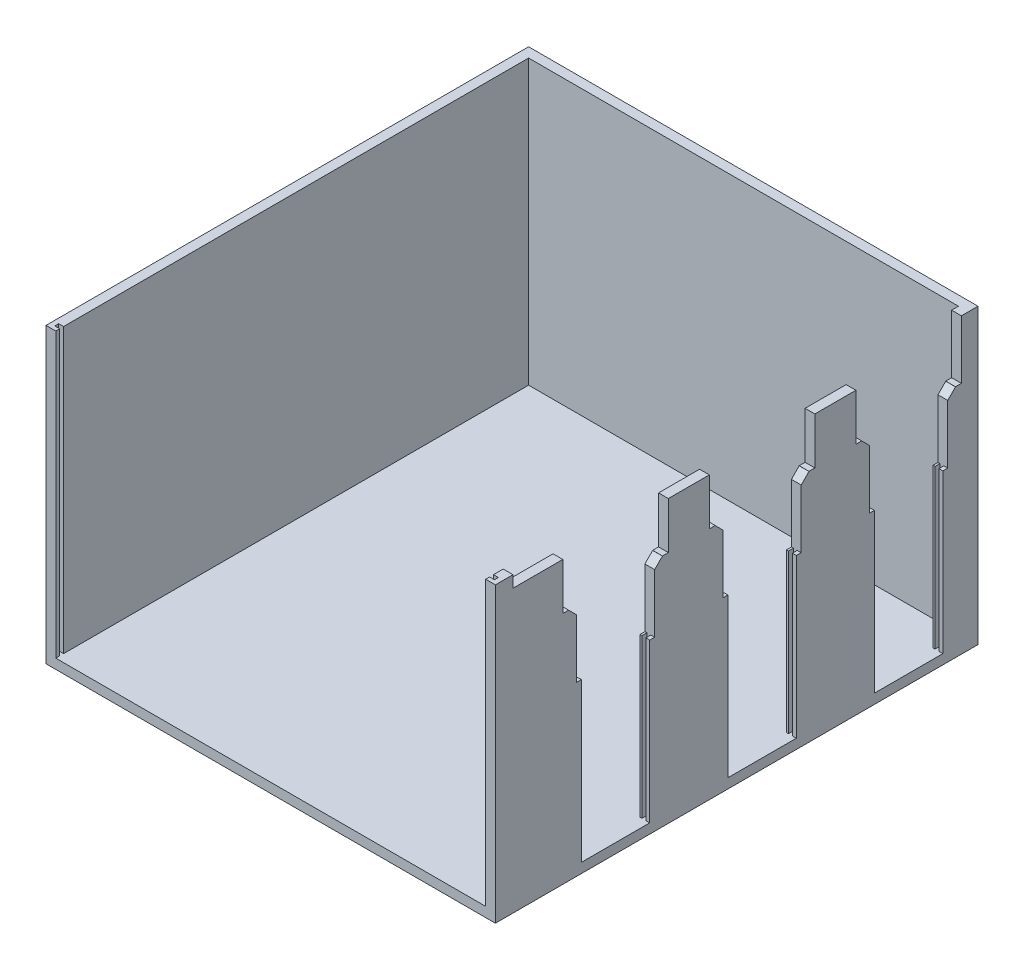
SolidWorks part; units mm, degrees
ref_plane "Płaszczyzna przednia" through (0, 0, 0) normal (0, 0, 1) x (1, 0, 0)
ref_plane "Płaszczyzna górna" through (0, 0, 0) normal (0, 1, 0) x (1, 0, 0)
ref_plane "Płaszczyzna prawa" through (0, 0, 0) normal (1, 0, 0) x (0, 0, -1)
sketch "Szkic1" plane through (0, 0, 0) normal (0, 0, 1) x (1, 0, 0)
  line L1 (-115, -75) -> (115, -75)
  line L2 (-115, -75) -> (-115, 75)
  line L3 (-115, 75) -> (115, 75)
  line L4 (115, -75) -> (115, 75)
  line L5 (0, 75) -> (0, -75) construction
  line L6 (-115, 0) -> (115, 0) construction
  point P0 (0, 0)
  dimension "D1" = 230
  dimension "D2" = 150
extrude "Dodanie-wyciągnięcie1" add sketch "Szkic1" along normal blind 5
sketch "Szkic3" plane through (0, 0, 5) normal (0, 0, 1) x (1, 0, 0)
  line L4 (115, -75) -> (115, 75)
  line L5 (115, 75) -> (-115, 75)
  line L6 (-115, 75) -> (-115, -75)
  line L7 (-115, -75) -> (115, -75)
  line L8 (115, -75) -> (115, 75)
  line L9 (115, 75) -> (110, 75)
  line L10 (-115, 75) -> (-115, -75)
  line L11 (-115, -75) -> (115, -75)
  line L12 (-110, 70) -> (-110, 75)
  line L13 (110, 70) -> (110, 75)
  line L14 (-110, 75) -> (-115, 75)
  line L16 (110, -70) -> (110, 70)
  line L17 (110, 70) -> (-110, 70)
  line L18 (-110, 70) -> (-110, -70)
  line L19 (-110, -70) -> (110, -70)
  line L20 (110, -70) -> (110, 70)
  line L22 (-110, 70) -> (-110, -70)
  line L23 (-110, -70) -> (110, -70)
  dimension "D1" = 0
  dimension "D2" = 5
extrude "Dodanie-wyciągnięcie2" add sketch "Szkic3" along normal blind 242
sketch "Szkic4" plane through (115, 0, 0) normal (1, 0, 0) x (0, 0, -1)
  line L0 (-247, 75) -> (0, 75) construction
  line L1 (-238, 75) -> (-208, 75)
  line L2 (-163, 75) -> (-133, 75)
  line L3 (-88, 75) -> (-58, 75)
  line L16 (-133, 69) -> (-163, 69)
  line L17 (-163, 69) -> (-163, 93)
  line L18 (-163, 93) -> (-208, 93)
  line L19 (-208, 93) -> (-208, 69)
  line L20 (-208, 69) -> (-238, 69)
  line L21 (-238, 69) -> (-238, 93)
  line L22 (-238, 93) -> (-242, 93)
  line L23 (-242, 93) -> (-242, 65)
  line L24 (-242, 65) -> (-5, 65)
  line L25 (-5, 65) -> (-5, 93)
  line L26 (-5, 93) -> (-58, 93)
  line L27 (-58, 93) -> (-58, 69)
  line L28 (-58, 69) -> (-88, 69)
  line L29 (-88, 69) -> (-88, 93)
  line L30 (-88, 93) -> (-133, 93)
  line L31 (-133, 93) -> (-133, 69)
  line L32 (-133, 69) -> (-163, 69)
  line L33 (-163, 69) -> (-163, 75)
  line L35 (-208, 75) -> (-208, 69)
  line L36 (-208, 69) -> (-238, 69)
  line L37 (-238, 69) -> (-238, 75)
  line L43 (-58, 75) -> (-58, 69)
  line L44 (-58, 69) -> (-88, 69)
  line L45 (-88, 69) -> (-88, 75)
  line L47 (-133, 75) -> (-133, 69)
  dimension "D1" = 0
extrude "Wytnij-wyciągnięcie1" cut sketch "Szkic4" against normal up to next
sketch "Szkic6" plane through (115, 0, 0) normal (1, 0, 0) x (0, 0, -1)
  line L0 (-62.5, 65) -> (-62.5, 69)
  line L1 (-59.5, 45.0546) -> (-59.5, 45)
  line L2 (-8.5, 65) -> (-8.5, 75)
  line L3 (-137.5, 65) -> (-137.5, 69)
  line L4 (-58.5, 44) -> (-55.5, 41)
  line L5 (-55.5, 41) -> (-54.5, 41)
  line L6 (-54.5, 41) -> (-54.5, 44)
  line L7 (-54.5, 44) -> (-58.5, 44)
  line L8 (-58.5, 44) -> (-55.5, 41)
  line L12 (-62.5, 65) -> (-62.5, 45.0546)
  line L13 (-62.5, 45.0546) -> (-55.7121, 45.0546)
  line L14 (-55.7121, 45.0546) -> (-55.7121, 45.7879)
  line L15 (-55.7121, 45.7879) -> (-59.8, 49.8757)
  line L16 (-59.8, 49.8757) -> (-59.8, 51)
  line L17 (-59.8, 51) -> (-11.2, 51)
  line L18 (-11.2, 51) -> (-11.2, 49.8757)
  line L19 (-11.2, 49.8757) -> (-15.2879, 45.7879)
  line L20 (-15.5, 41) -> (-16.5, 41)
  line L21 (-16.5, 41) -> (-16.5, 51)
  line L22 (-16.5, 51) -> (-20.5, 51)
  line L23 (-20.5, 51) -> (-20.5, 50.5)
  line L24 (-20.5, 50.5) -> (-18.2071, 48.2071)
  line L25 (-18.2071, 46.7929) -> (-20.5, 44.5)
  line L26 (-20.5, 44.5) -> (-39.5, 44.5)
  line L27 (-39.5, 44.5) -> (-39.5, 34.5)
  line L28 (-39.5, 34.5) -> (-43.5, 34.5)
  line L29 (-43.5, 34.5) -> (-43.5, 44.5)
  line L30 (-43.5, 44.5) -> (-50.5, 44.5)
  line L31 (-50.5, 44.5) -> (-52.7929, 46.7929)
  line L32 (-52.7929, 48.2071) -> (-50.5, 50.5)
  line L33 (-50.5, 50.5) -> (-50.5, 51)
  line L34 (-50.5, 51) -> (-54.5, 51)
  line L35 (-54.5, 51) -> (-54.5, 41)
  line L36 (-54.5, 41) -> (-55.5, 41)
  line L37 (-55.5, 41) -> (-55.5, 11)
  line L38 (-55.5, 11) -> (-15.5, 11)
  line L39 (-15.5, 11) -> (-15.5, 41)
  line L57 (-55.5, 41) -> (-55.5, 11)
  line L58 (-55.5, 11) -> (-15.5, 11)
  line L59 (-15.5, 11) -> (-15.5, 41)
  line L60 (-15.2879, 45.7879) -> (-15.2879, 45.0546)
  line L61 (-15.2879, 45.0546) -> (-8.5, 45.0546)
  line L62 (-8.5, 45.0546) -> (-8.5, 65)
  line L63 (-8.5, 65) -> (-62.5, 65)
  line L64 (-62.5, 65) -> (-62.5, 45.0546)
  line L65 (-62.5, 45.0546) -> (-59.5, 45.0546)
  line L73 (-11.5, 45.0546) -> (-8.5, 45.0546)
  line L74 (-8.5, 45.0546) -> (-8.5, 65)
  line L76 (-15.5, 41) -> (-12.5, 44)
  line L77 (-12.5, 44) -> (-16.5, 44)
  line L78 (-16.5, 44) -> (-16.5, 41)
  line L79 (-16.5, 41) -> (-15.5, 41)
  line L80 (-15.5, 41) -> (-12.5, 44)
  line L84 (-134.5, 45.0546) -> (-134.5, 45)
  line L85 (-59.5, 45) -> (-58.5, 44)
  line L86 (-58.5, 44) -> (-54.5, 44)
  line L87 (-54.5, 44) -> (-54.5, 51)
  line L88 (-54.5, 51) -> (-59.5, 51)
  line L89 (-59.5, 51) -> (-59.5, 45)
  line L90 (-59.5, 45) -> (-58.5, 44)
  line L95 (-16.5, 51) -> (-16.5, 44)
  line L96 (-16.5, 44) -> (-12.5, 44)
  line L97 (-12.5, 44) -> (-11.5, 45)
  line L98 (-11.5, 45) -> (-11.5, 51)
  line L99 (-11.5, 51) -> (-16.5, 51)
  line L102 (-12.5, 44) -> (-11.5, 45)
  line L103 (-11.5, 45) -> (-11.5, 45.0546)
  line L105 (-83.5, 65) -> (-83.5, 69)
  line L106 (-133.5, 44) -> (-130.5, 41)
  line L107 (-130.5, 41) -> (-130.5, 11)
  line L108 (-130.5, 11) -> (-90.5, 11)
  line L109 (-90.5, 11) -> (-90.5, 41)
  line L110 (-137.5, 65) -> (-137.5, 45.0546)
  line L111 (-137.5, 45.0546) -> (-134.5, 45.0546)
  line L112 (-86.5, 45.0546) -> (-83.5, 45.0546)
  line L113 (-83.5, 45.0546) -> (-83.5, 65)
  line L114 (-90.5, 41) -> (-87.5, 44)
  line L115 (-134.5, 45) -> (-133.5, 44)
  line L116 (-87.5, 44) -> (-86.5, 45)
  line L117 (-58, 69) -> (-88, 69)
  line L118 (-88, 69) -> (-88, 75)
  line L119 (-88, 75) -> (-133, 75)
  line L120 (-133, 75) -> (-133, 69)
  line L121 (-133, 69) -> (-163, 69)
  line L122 (-163, 69) -> (-163, 75)
  line L123 (-163, 75) -> (-208, 75)
  line L124 (-208, 75) -> (-208, 69)
  line L125 (-208, 69) -> (-238, 69)
  line L126 (-238, 69) -> (-238, 75)
  line L127 (-238, 75) -> (-247, 75)
  line L128 (-247, 75) -> (-247, -75)
  line L129 (-247, -75) -> (0, -75)
  line L130 (0, -75) -> (0, 75)
  line L131 (0, 75) -> (-58, 75)
  line L132 (-58, 75) -> (-58, 69)
  line L133 (-58, 69) -> (-62.5, 69)
  line L134 (-88, 69) -> (-88, 75)
  line L135 (-88, 75) -> (-133, 75)
  line L136 (-133, 75) -> (-133, 69)
  line L137 (-133, 69) -> (-137.5, 69)
  line L138 (-163, 69) -> (-163, 75)
  line L139 (-163, 75) -> (-208, 75)
  line L140 (-208, 75) -> (-208, 69)
  line L141 (-208, 69) -> (-212.5, 69)
  line L147 (-8.5, 75) -> (-58, 75)
  line L148 (-58, 75) -> (-58, 69)
  line L149 (-86.5, 45) -> (-86.5, 45.0546)
  line L150 (-133, 75) -> (-133, 69)
  line L151 (-212.5, 65) -> (-212.5, 69)
  line L152 (-209.5, 45.0546) -> (-209.5, 45)
  line L153 (-158.5, 65) -> (-158.5, 69)
  line L154 (-208.5, 44) -> (-205.5, 41)
  line L155 (-205.5, 41) -> (-205.5, 11)
  line L156 (-205.5, 11) -> (-165.5, 11)
  line L157 (-165.5, 11) -> (-165.5, 41)
  line L158 (-212.5, 65) -> (-212.5, 45.0546)
  line L159 (-212.5, 45.0546) -> (-209.5, 45.0546)
  line L160 (-161.5, 45.0546) -> (-158.5, 45.0546)
  line L161 (-158.5, 45.0546) -> (-158.5, 65)
  line L162 (-165.5, 41) -> (-162.5, 44)
  line L163 (-209.5, 45) -> (-208.5, 44)
  line L164 (-162.5, 44) -> (-161.5, 45)
  line L165 (-161.5, 45) -> (-161.5, 45.0546)
  line L166 (-208, 75) -> (-208, 69)
  line L167 (-83.5, 69) -> (-88, 69)
  line L168 (-158.5, 69) -> (-163, 69)
  arc A2 (-18.2071, 46.7929) -> (-18.2071, 48.2071) centre (-18.9142, 47.5) ccw
  arc A3 (-52.7929, 48.2071) -> (-52.7929, 46.7929) centre (-52.0858, 47.5) ccw
  dimension "D9" = 75
  dimension "D1" = 0
  dimension "D2" = 0
  dimension "D3" = 0
  dimension "D4" = 0
  dimension "D5" = 0
  dimension "D6" = 0
  dimension "D7" = 0
  dimension "D8" = 3
extrude "Wytnij-wyciągnięcie2" cut sketch "Szkic6" against normal up to surface (5 mm away)
sketch "Szkic7" plane through (0, 75, 0) normal (0, 1, 0) x (1, 0, 0)
  line L0 (-110, -245) -> (-112.5, -245)
  line L1 (-110, -247) -> (-110, -5) construction
  line L2 (-112.5, -245) -> (-112.5, -243)
  line L3 (-112.5, -243) -> (-110, -243)
  line L4 (-110, -247) -> (-110, -5) construction
  line L5 (-110, -247) -> (-115, -247) construction
  line L6 (-110, -243) -> (-110, -245)
  line L7 (0, -247) -> (0, -5) construction
  line L8 (110, -247) -> (-110, -247) construction
  line L9 (110, -5) -> (-110, -5) construction
  line L10 (110, -243) -> (110, -245)
  line L11 (112.5, -243) -> (110, -243)
  line L12 (112.5, -245) -> (112.5, -243)
  line L13 (110, -245) -> (112.5, -245)
  line L14 (111, -205.5) -> (111, -203)
  line L16 (113, -203) -> (113, -205.5)
  line L17 (110, -185.5) -> (115, -185.5) construction
  line L18 (110, -165.5) -> (110, -205.5)
  line L19 (110, -205.5) -> (115, -205.5)
  line L20 (115, -205.5) -> (115, -165.5)
  line L21 (115, -165.5) -> (110, -165.5)
  line L22 (110, -165.5) -> (110, -205.5)
  line L23 (110, -205.5) -> (115, -205.5)
  line L24 (115, -205.5) -> (115, -165.5)
  line L25 (115, -165.5) -> (110, -165.5)
  line L26 (113, -205.5) -> (111, -205.5)
  line L27 (113, -165.5) -> (111, -165.5)
  line L28 (113, -168) -> (113, -165.5)
  line L30 (111, -165.5) -> (111, -168)
  line L31 (113, -168) -> (115, -168)
  line L32 (111, -168) -> (110, -168)
  line L33 (111, -203) -> (110, -203)
  line L34 (113, -203) -> (115, -203)
  line L35 (111, -130.5) -> (111, -128)
  line L36 (113, -128) -> (113, -130.5)
  line L37 (110, -90.5) -> (110, -130.5)
  line L38 (110, -130.5) -> (115, -130.5)
  line L39 (115, -130.5) -> (115, -90.5)
  line L40 (115, -90.5) -> (110, -90.5)
  line L41 (113, -130.5) -> (111, -130.5)
  line L42 (113, -90.5) -> (111, -90.5)
  line L43 (113, -93) -> (113, -90.5)
  line L44 (111, -90.5) -> (111, -93)
  line L45 (113, -93) -> (115, -93)
  line L46 (111, -93) -> (110, -93)
  line L47 (111, -128) -> (110, -128)
  line L48 (113, -128) -> (115, -128)
  line L49 (110, -110.5) -> (115, -110.5) construction
  line L50 (111, -55.5) -> (111, -53)
  line L51 (113, -53) -> (113, -55.5)
  line L52 (110, -15.5) -> (110, -55.5)
  line L53 (110, -55.5) -> (115, -55.5)
  line L54 (115, -55.5) -> (115, -15.5)
  line L55 (115, -15.5) -> (110, -15.5)
  line L56 (113, -55.5) -> (111, -55.5)
  line L57 (113, -15.5) -> (111, -15.5)
  line L58 (113, -18) -> (113, -15.5)
  line L59 (111, -15.5) -> (111, -18)
  line L60 (113, -18) -> (115, -18)
  line L61 (111, -18) -> (110, -18)
  line L62 (111, -53) -> (110, -53)
  line L63 (113, -53) -> (115, -53)
  line L64 (110, -35.5) -> (115, -35.5) construction
  point P10 (-111.25, -245)
  line M57 (-110, -247) -> (-110, -5)
  dimension "D1" = 2
  dimension "D2" = 2
  dimension "D3" = 2.5
  dimension "D5" = 2
  dimension "D6" = 2
  dimension "D7" = 2.5
  dimension "D9" = 75
  dimension "D4" = 0
  dimension "D8" = 3
extrude "Wytnij-wyciągnięcie3" cut sketch "Szkic7" along direction (0, -1, 0) on the side against the normal up to surface (145 mm away) contours L3 L2 L0 M57 | L10 L13 L12 L11 | L16 L34 L24 L31 L28 L25 L30 L32 L22 L33 L14 L23 | L36 L48 L39 L45 L43 L40 L44 L46 L37 L47 L35 L38 | L51 L63 L54 L60 L58 L55 L59 L61 L52 L62 L50 L53
